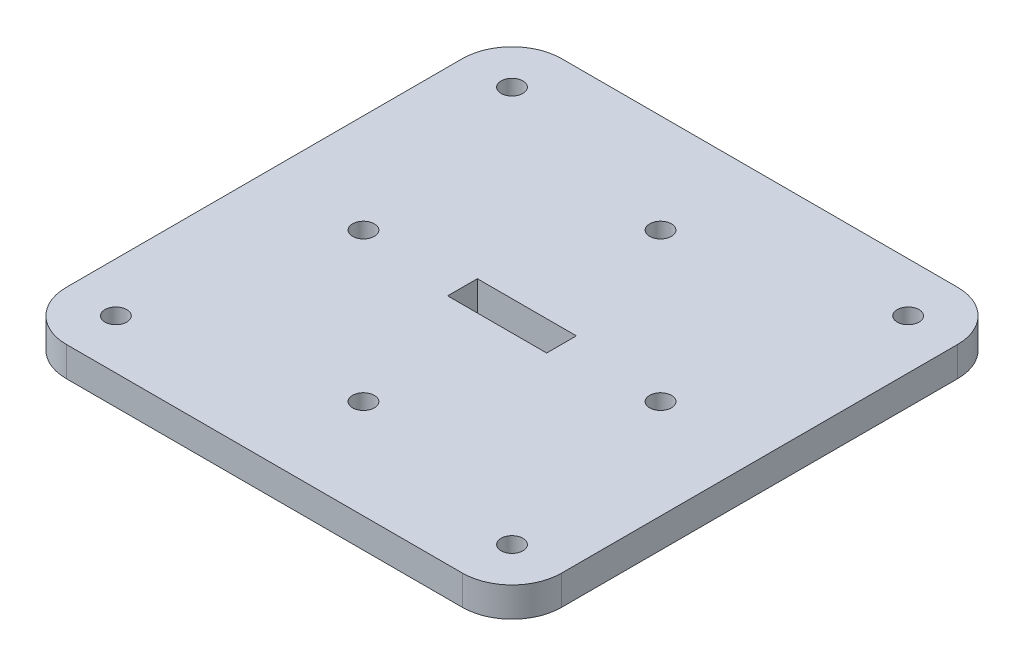
SolidWorks part; units mm, degrees
ref_plane "Front Plane" through (0, 0, 0) normal (0, 0, 1) x (1, 0, 0)
ref_plane "Top Plane" through (0, 0, 0) normal (0, 1, 0) x (1, 0, 0)
ref_plane "Right Plane" through (0, 0, 0) normal (1, 0, 0) x (0, 0, -1)
sketch "Sketch1" plane through (0, 0, 0) normal (0, 1, 0) x (1, 0, 0)
  line L0 (0, 25) -> (0, -25) construction
  line L1 (-25, -25) -> (25, -25)
  line L2 (-25, -25) -> (-25, 25)
  line L3 (-25, 25) -> (25, 25)
  line L4 (25, -25) -> (25, 25)
  line L5 (-25, -25) -> (25, 25) construction
  line L6 (-25, 25) -> (25, -25) construction
  line L7 (-25, 0) -> (25, 0) construction
  line L8 (-5, -1.5) -> (5, -1.5)
  line L9 (-5, -1.5) -> (-5, 1.5)
  line L10 (-5, 1.5) -> (5, 1.5)
  line L11 (5, -1.5) -> (5, 1.5)
  line L12 (-5, -1.5) -> (5, 1.5) construction
  line L13 (-5, 1.5) -> (5, -1.5) construction
  circle A0 centre (-15, 0) radius 1.1
  circle A2 centre (15, 0) radius 1.1
  circle A3 centre (-20, 20) radius 1.1
  circle A4 centre (20, 20) radius 1.1
  circle A5 centre (20, -20) radius 1.1
  circle A6 centre (-20, -20) radius 1.1
  circle A7 centre (0, 15) radius 1.1
  circle A8 centre (0, -15) radius 1.1
  point P0 (0, 0)
  point P13 (0, 0)
  dimension "D3" = 15
  dimension "D4" = 2.2
  dimension "D7" = 2.2
  dimension "D10" = 2.2
  dimension "D1" = 50
  dimension "D2" = 50
  dimension "D5" = 10
  dimension "D6" = 3
  dimension "D8" = 5
  dimension "D9" = 5
  dimension "D11" = 15
extrude "Boss-Extrude1" add sketch "Sketch1" along normal blind 3
fillet "Fillet1" radius 5 4 edges at (25, 1.5, -25) (-25, 1.5, -25) (-25, 1.5, 25) (25, 1.5, 25)
